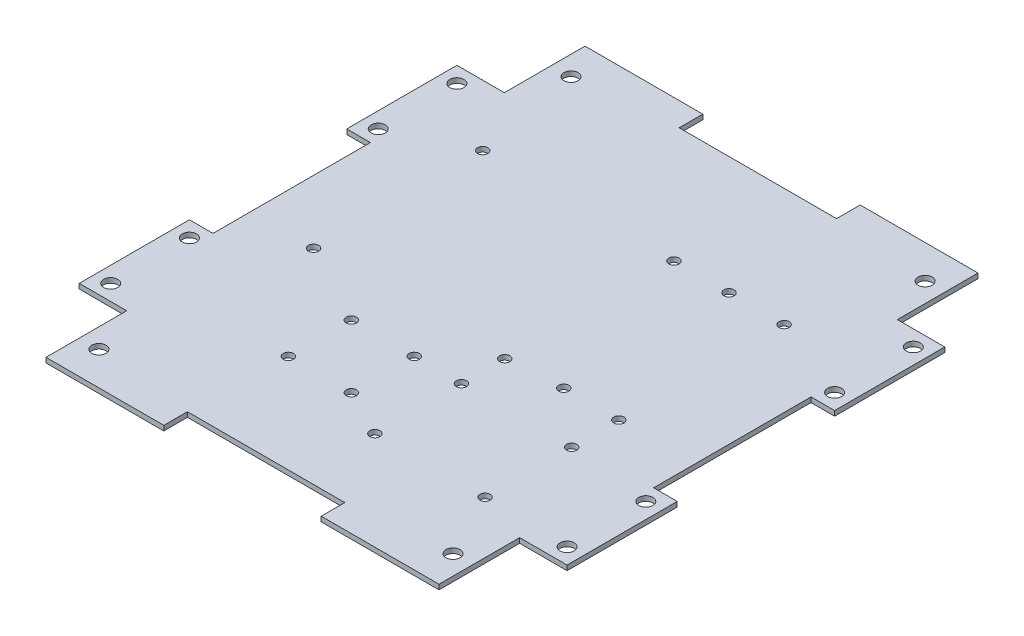
SolidWorks part; units mm, degrees
ref_plane "Front Plane" through (0, 0, 0) normal (0, 0, 1) x (1, 0, 0)
ref_plane "Top Plane" through (0, 0, 0) normal (0, 1, 0) x (1, 0, 0)
ref_plane "Right Plane" through (0, 0, 0) normal (1, 0, 0) x (0, 0, -1)
sketch "Sketch1" plane through (0, 0, 0) normal (0, 1, 0) x (1, 0, 0)
  line L0 (-25.4, 86.995) -> (-63.4314, 86.995)
  line L1 (-88.9, -101.6) -> (88.9, -101.6) construction
  line L2 (101.6, -88.9) -> (101.6, 88.9) construction
  line L3 (88.9, 101.6) -> (-88.9, 101.6) construction
  line L4 (-78.74, -60.96) -> (-63.4314, -60.96)
  line L5 (-63.4314, -60.96) -> (-63.4314, -86.995)
  line L6 (-63.4314, -86.995) -> (-25.4, -86.995)
  line L7 (63.4314, -86.995) -> (63.4314, -60.96)
  line L8 (63.4314, -60.96) -> (78.74, -60.96)
  line L9 (78.74, -60.96) -> (78.74, -25.4)
  line L10 (78.74, 60.96) -> (63.4314, 60.96)
  line L11 (63.4314, 60.96) -> (63.4314, 86.995)
  line L12 (63.4314, 86.995) -> (25.4, 86.995)
  line L13 (-63.4314, 86.995) -> (-63.4314, 60.96)
  line L14 (-63.4314, 60.96) -> (-78.74, 60.96)
  line L15 (-78.74, 60.96) -> (-78.74, 25.4)
  line L16 (-78.74, -25.4) -> (-78.74, -60.96)
  line L17 (-78.74, -25.4) -> (-71.12, -25.4)
  line L19 (-78.74, 25.4) -> (-71.12, 25.4)
  line L20 (-71.12, -25.4) -> (-71.12, 25.4)
  line L22 (-25.4, 86.995) -> (-25.4, 79.375)
  line L23 (-25.4, 79.375) -> (25.4, 79.375)
  line L24 (25.4, 86.995) -> (25.4, 79.375)
  line L25 (78.74, 25.4) -> (71.12, 25.4)
  line L27 (78.74, -25.4) -> (71.12, -25.4)
  line L28 (71.12, 25.4) -> (71.12, -25.4)
  line L30 (25.4, -86.995) -> (25.4, -79.375)
  line L31 (25.4, -79.375) -> (-25.4, -79.375)
  line L32 (-25.4, -86.995) -> (-25.4, -79.375)
  line L33 (78.74, 25.4) -> (78.74, 60.96)
  line L34 (25.4, -86.995) -> (63.4314, -86.995)
  line L35 (-101.6, 88.9) -> (-101.6, -88.9) construction
  arc A0 (88.9, -101.6) -> (101.6, -88.9) centre (88.9, -88.9) ccw construction
  arc A1 (-101.6, -88.9) -> (-88.9, -101.6) centre (-88.9, -88.9) ccw construction
  arc A2 (101.6, 88.9) -> (88.9, 101.6) centre (88.9, 88.9) ccw construction
  arc A3 (-101.6, 88.9) -> (-88.9, 101.6) centre (-88.9, 88.9) cw construction
  circle A4 centre (-57.15, 76.2) radius 2.286
  circle A5 centre (57.15, 76.2) radius 2.286
  circle A6 centre (57.15, -76.2) radius 2.286
  circle A7 centre (-57.15, -76.2) radius 2.286
  point P3 (0, 101.6)
  point P5 (101.6, 0)
  point P13 (101.6, 101.6)
  point P16 (-101.6, 101.6)
  point P38 (-71.12, 0)
  point P55 (0, -79.375)
  point P56 (0, 79.375)
  point P57 (71.12, 0)
  dimension "D2" = 12.7
  dimension "D11" = 4.572
  dimension "D8" = 44.45
  dimension "D1" = 203.2
  dimension "D3" = 203.2
  dimension "D4" = 22.86
  dimension "D5" = 15.3086
  dimension "D6" = 35.56
  dimension "D7" = 173.99
  dimension "D12" = 50.8
  dimension "D13" = 25.4
  dimension "D14" = 44.45
  dimension "D15" = 25.4
  dimension "D18" = 7.62
extrude "Boss-Extrude1" add sketch "Sketch1" along normal blind 1.5875
sketch "Sketch2" plane through (0, 1.5875, 0) normal (0, 1, 0) x (1, 0, 0)
  line L0 (0, -1000) -> (0, 49000) construction
  line L1 (-1000, 0) -> (49000, 0) construction
  line L2 (-78.74, -60.96) -> (-63.4314, -60.96) construction
  line L3 (-71.12, -25.4) -> (-78.74, -25.4) construction
  line L4 (-78.74, -25.4) -> (-78.74, -60.96) construction
  circle A0 centre (-73.66, -30.48) radius 2.286
  circle A1 centre (-73.66, -55.88) radius 2.286
  circle A2 centre (73.66, -55.88) radius 2.286
  circle A3 centre (73.66, -30.48) radius 2.286
  circle A4 centre (73.66, 30.48) radius 2.286
  circle A5 centre (73.66, 55.88) radius 2.286
  circle A6 centre (-73.66, 55.88) radius 2.286
  circle A7 centre (-73.66, 30.48) radius 2.286
  dimension "D1" = 4.572
  dimension "D2" = 5.08
  dimension "D3" = 5.08
  dimension "D4" = 5.08
extrude "Cut-Extrude1" cut sketch "Sketch2" against normal through all
sketch "Sketch3" plane through (0, 1.5875, 0) normal (0, 1, 0) x (1, 0, 0)
  line L0 (-63.4314, 86.995) -> (-63.4314, 60.96) construction
  line L1 (-50.7314, 41.275) -> (10.9906, 41.275) construction
  line L2 (-50.7314, 41.275) -> (-50.7314, -13.335) construction
  line L3 (-50.7314, -13.335) -> (10.9906, -13.335) construction
  line L4 (10.9906, 41.275) -> (10.9906, -13.335) construction
  line L5 (25.4, 79.375) -> (-25.4, 79.375) construction
  circle A0 centre (-50.7314, 41.275) radius 1.651
  circle A1 centre (10.9906, 41.275) radius 1.651
  circle A2 centre (10.9906, -13.335) radius 1.651
  circle A3 centre (-50.7314, -13.335) radius 1.651
  dimension "D3" = 3.302
  dimension "D1" = 54.61
  dimension "D2" = 61.722
  dimension "D4" = 12.7
  dimension "D5" = 38.1
extrude "Lipo Holder Holes" cut sketch "Sketch3" against normal through all
sketch "Sketch4" plane through (0, 1.5875, 0) normal (0, 1, 0) x (1, 0, 0)
  line L0 (46.5506, -12.065) -> (28.7706, -12.065) construction
  line L1 (49.0906, 43.815) -> (26.2306, 43.815) construction
  line L2 (49.0906, 43.815) -> (49.0906, -14.605) construction
  line L3 (49.0906, -14.605) -> (26.2306, -14.605) construction
  line L4 (26.2306, 43.815) -> (26.2306, -14.605) construction
  line L5 (28.7706, -12.065) -> (28.7706, 41.275) construction
  circle A0 centre (28.7706, 41.275) radius 1.651
  circle A1 centre (46.5506, 41.275) radius 1.651
  circle A2 centre (46.5506, -12.065) radius 1.651
  circle A3 centre (28.7706, -12.065) radius 1.651
  circle A4 centre (10.9906, 41.275) radius 1.651 construction
  circle A5 centre (10.9906, 41.275) radius 1.651
  point P10 (0, 0)
  point P12 (0, 0)
  point P14 (0, 0)
  point P15 (0, 0)
  point P16 (37.6606, -12.065)
  point P17 (37.6606, -14.605)
  point P18 (28.7706, 14.605)
  point P19 (26.2306, 14.605)
  point P23 (0, 0)
  point P24 (0, 0)
  dimension "D5" = 3.302
  dimension "D1" = 22.86
  dimension "D2" = 58.42
  dimension "D3" = 2.54
  dimension "D4" = 2.54
  dimension "D6" = 15.24
extrude "LoRa Thing Plus" cut sketch "Sketch4" against normal through all
sketch "Sketch5" plane through (0, 1.5875, 0) normal (0, 1, 0) x (1, 0, 0)
  line L0 (46.5506, -55.245) -> (46.5506, -27.305) construction
  line L1 (49.0906, -57.785) -> (8.4506, -57.785) construction
  line L2 (49.0906, -57.785) -> (49.0906, -24.765) construction
  line L3 (49.0906, -24.765) -> (8.4506, -24.765) construction
  line L4 (8.4506, -57.785) -> (8.4506, -24.765) construction
  line L5 (46.5506, -27.305) -> (10.9906, -27.305) construction
  circle A0 centre (46.5506, -55.245) radius 1.651
  circle A1 centre (10.9906, -55.245) radius 1.651
  circle A2 centre (10.9906, -27.305) radius 1.651
  circle A3 centre (46.5506, -27.305) radius 1.651
  circle A4 centre (46.5506, -12.065) radius 1.651 construction
  circle A5 centre (46.5506, -12.065) radius 1.651
  point P12 (0, 0)
  point P13 (0, 0)
  point P14 (46.5506, -41.275)
  point P15 (49.0906, -41.275)
  point P16 (28.7706, -27.305)
  point P17 (28.7706, -24.765)
  point P21 (0, 0)
  dimension "D5" = 3.302
  dimension "D6" = 12.7
  dimension "D1" = 40.64
  dimension "D2" = 33.02
  dimension "D3" = 35.56
  dimension "D4" = 27.94
extrude "GPS Breakout Board" cut sketch "Sketch5" against normal through all and the other way through all
sketch "Sketch6" plane through (0, 1.5875, 0) normal (0, 1, 0) x (1, 0, 0)
  line L0 (-4.2494, -47.625) -> (-24.5694, -47.625) construction
  line L1 (-1.7094, -50.165) -> (-27.1094, -50.165) construction
  line L2 (-1.7094, -50.165) -> (-1.7094, -24.765) construction
  line L3 (-1.7094, -24.765) -> (-27.1094, -24.765) construction
  line L4 (-27.1094, -50.165) -> (-27.1094, -24.765) construction
  line L5 (-24.5694, -47.625) -> (-24.5694, -27.305) construction
  circle A0 centre (-4.2494, -47.625) radius 1.651
  circle A1 centre (-24.5694, -47.625) radius 1.651
  circle A2 centre (-24.5694, -27.305) radius 1.651
  circle A3 centre (-4.2494, -27.305) radius 1.651
  circle A4 centre (10.9906, -27.305) radius 1.651 construction
  circle A5 centre (10.9906, -27.305) radius 1.651
  point P12 (0, 0)
  point P13 (0, 0)
  point P14 (-24.5694, -37.465)
  point P15 (-27.1094, -37.465)
  point P16 (-14.4094, -47.625)
  point P17 (-14.4094, -50.165)
  point P21 (0, 0)
  dimension "D3" = 3.302
  dimension "D6" = 12.7
  dimension "D1" = 25.4
  dimension "D2" = 25.4
  dimension "D4" = 2.54
  dimension "D5" = 2.54
extrude "Cut-Extrude4" cut sketch "Sketch6" against normal through all
